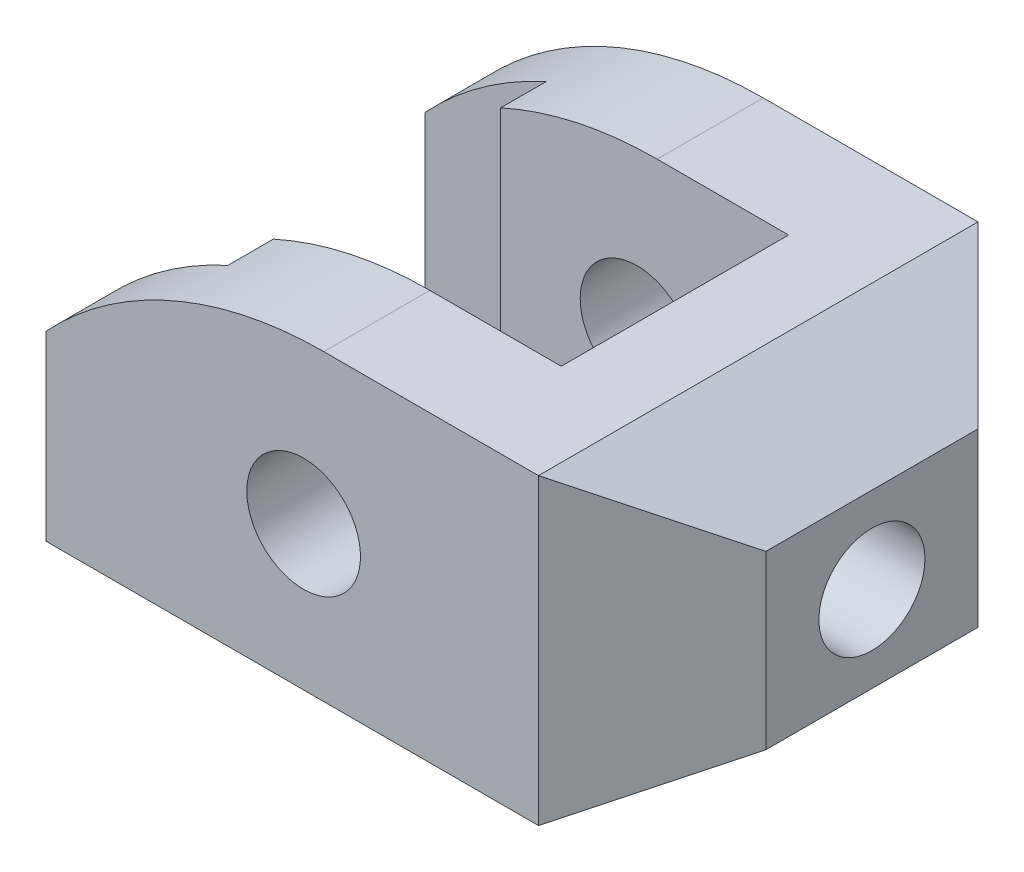
SolidWorks part; units mm, degrees
material "1060 Alloy"
ref_plane "Front Plane" through (0, 0, 0) normal (0, 0, 1) x (1, 0, 0)
ref_plane "Top Plane" through (0, 0, 0) normal (0, 1, 0) x (1, 0, 0)
ref_plane "Right Plane" through (0, 0, 0) normal (1, 0, 0) x (0, 0, -1)
sketch "Sketch3" plane through (0, 0, 0) normal (0, 0, 1) x (1, 0, 0)
  line L0 (0, -42.6875) -> (0, 42.6875) construction
  line L1 (46, 0) -> (-46, 0) construction
  line L2 (-34, 5) -> (-34, -19)
  line L3 (-34, -19) -> (31, -19)
  line L4 (31, -19) -> (46, -10.3397)
  line L5 (46, -10.3397) -> (46, 12.3397)
  line L6 (46, 12.3397) -> (31, 21)
  line L7 (31, 21) -> (2.6606, 21)
  line L8 (31, -19) -> (49.0647, -19) construction
  line L9 (31, 21) -> (46, 21) construction
  circle A0 centre (0, 0) radius 7.5
  arc A1 (-34, 5) -> (2.6606, 21) centre (2.6606, -29) cw
  point P4 (0, 0)
  point P8 (0, 0)
  dimension "D1" = 15
  dimension "D11" = 50
  dimension "D2" = 24
  dimension "D3" = 65
  dimension "D4" = 40
  dimension "D5" = 19
  dimension "D6" = 31
  dimension "D7" = 15
  dimension "D8" = 30
  dimension "D9" = 30
  dimension "D10" = 15
extrude "Boss-Extrude2" add sketch "Sketch3" along normal blind 58
sketch "Sketch5" plane through (0, -19, 0) normal (0, -1, 0) x (1, 0, 0)
  line L0 (46, 29) -> (-38.6388, 29) construction
  line L1 (-34, 58) -> (31, 58) construction
  line L2 (-34, 0) -> (31, 0) construction
  line L3 (-34, 58) -> (-34, 0) construction
  line L4 (-34, 50) -> (-18, 50)
  line L5 (-18, 50) -> (-18, 44)
  line L6 (-18, 44) -> (20, 44)
  line L7 (20, 44) -> (20, 14)
  line L8 (20, 14) -> (-18, 14)
  line L9 (-18, 14) -> (-18, 8)
  line L10 (-18, 8) -> (-34, 8)
  line L12 (31, 58) -> (31, 0) construction
  line L13 (-34, 50) -> (-34, 8)
  point P3 (-38.6388, 29)
  dimension "D1" = 29
  dimension "D2" = 8
  dimension "D3" = 16
  dimension "D4" = 6
  dimension "D5" = 11
  dimension "D6" = 8
  dimension "D7" = 16
  dimension "D8" = 6
extrude "Cut-Extrude6" cut sketch "Sketch5" against normal blind 58
sketch "Sketch8" plane through (0, 0, 0) normal (0, 1, 0) x (1, 0, 0)
  line L0 (31, 0) -> (46, 0)
  line L1 (31, 0) -> (46, -15)
  line L2 (46, -58) -> (46, 0) construction
  line L3 (46, -15) -> (46, 0)
  line L4 (46, -58) -> (46, -43)
  line L5 (46, -43) -> (31, -58)
  line L6 (31, -58) -> (46, -58)
  dimension "D1" = 45
  dimension "D2" = 45
extrude "Cut-Extrude9" cut sketch "Sketch8" against normal mid plane 58
sketch "Sketch10" plane through (46, 0, 0) normal (1, 0, 0) x (0, 0, -1)
  line L0 (-29, 12.3397) -> (-29, -10.3397) construction
  line L1 (-43, 12.3397) -> (-15, 12.3397) construction
  line L2 (-43, -10.3397) -> (-15, -10.3397) construction
  line L3 (-43, 1) -> (-15, 1) construction
  line L4 (-43, -10.3397) -> (-43, 12.3397) construction
  line L5 (-15, -10.3397) -> (-15, 12.3397) construction
  circle A0 centre (-29, 1) radius 7
  dimension "D1" = 14
extrude "Cut-Extrude10" cut sketch "Sketch10" against normal mid plane 198
